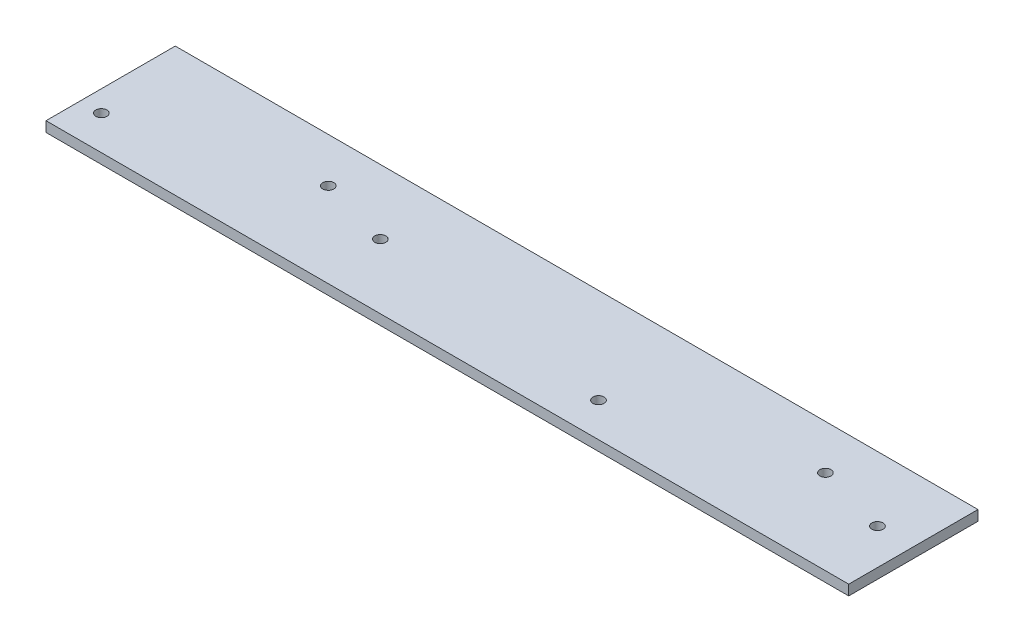
SolidWorks part; units mm, degrees
ref_plane "Front Plane" through (0, 0, 0) normal (0, 0, 1) x (1, 0, 0)
ref_plane "Top Plane" through (0, 0, 0) normal (0, 1, 0) x (1, 0, 0)
ref_plane "Right Plane" through (0, 0, 0) normal (1, 0, 0) x (0, 0, -1)
sketch "Sketch1" plane through (0, 0, 0) normal (0, 1, 0) x (1, 0, 0)
  line L0 (-71, -8.695) -> (71, -8.695) construction
  line L1 (0, 0) -> (0, 5.75) construction
  line L2 (-77.0457, -18.4656) -> (152.2561, -18.4656)
  line L3 (-77.0457, -18.4656) -> (-77.0457, 18.4656)
  line L4 (-77.0457, 18.4656) -> (152.2561, 18.4656)
  line L5 (152.2561, -18.4656) -> (152.2561, 18.4656)
  line L6 (71, -8.695) -> (142, -8.695) construction
  line L7 (142, -8.695) -> (142, 0) construction
  line L8 (0, 5.75) -> (-20.62, 5.75) construction
  line L9 (0, 0) -> (0, 14.6731) construction
  line L10 (142, 0) -> (142, 5.75) construction
  line L11 (142, 5.75) -> (121.38, 5.75) construction
  circle A0 centre (-71, -8.695) radius 1.5875
  circle A1 centre (71, -8.695) radius 1.5875
  circle A2 centre (0, 0) radius 1.5875
  circle A3 centre (-20.62, 5.75) radius 1.5875
  circle A4 centre (142, 0) radius 1.5875
  circle A5 centre (121.38, 5.75) radius 1.5875
  point P6 (0, 0)
  dimension "D2" = 3.175
  dimension "D1" = 142
  dimension "D3" = 5.75
  dimension "D4" = 20.62
  dimension "D5" = 8.695
  dimension "D6" = 8.695
  dimension "D7" = 71
  dimension "D8" = 20.62
  dimension "D9" = 5.75
extrude "Boss-Extrude1" add sketch "Sketch1" along normal mid plane 2.921
sketch "Sketch2" plane through (0, -1.4605, 0) normal (0, -1, 0) x (-1, 0, 0)
  line L0 (20.62, 5.75) -> (13.8061, 5.75) construction
